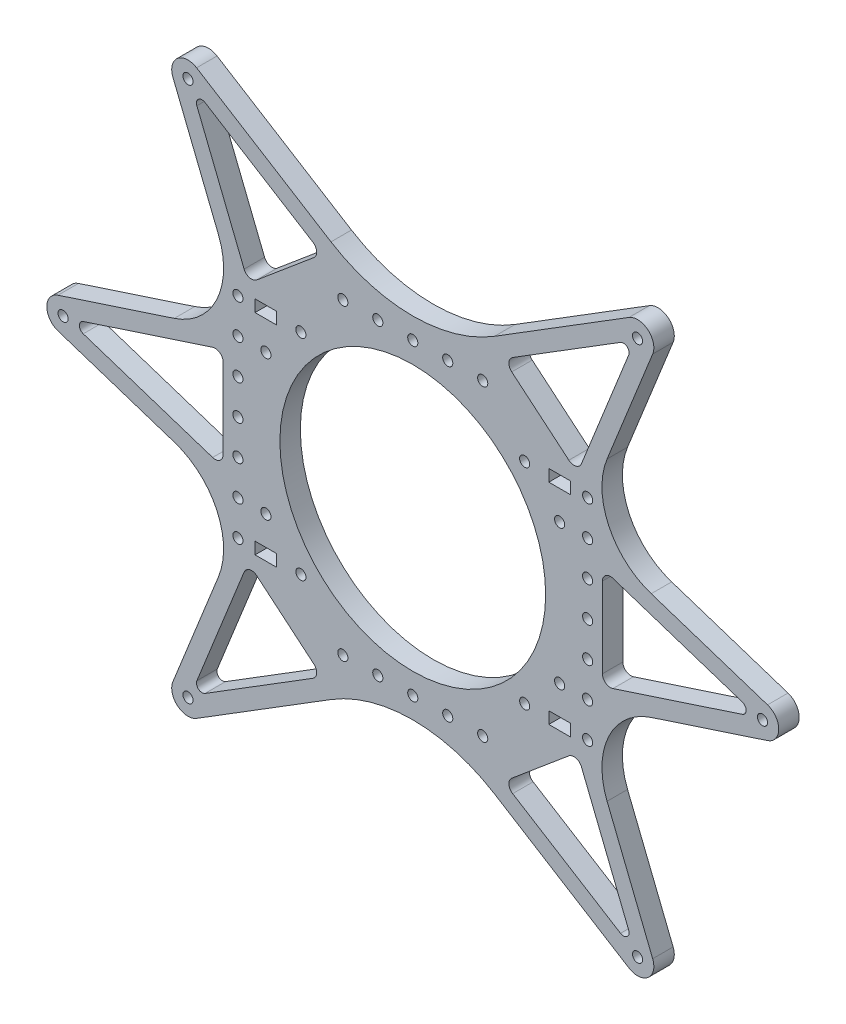
SolidWorks part; units mm, degrees
material "Acrylic (Medium-high impact)"
ref_plane "Front Plane" through (0, 0, 0) normal (0, 0, 1) x (1, 0, 0)
ref_plane "Top Plane" through (0, 0, 0) normal (0, 1, 0) x (1, 0, 0)
ref_plane "Right Plane" through (0, 0, 0) normal (1, 0, 0) x (0, 0, -1)
sketch "Sketch1" plane through (0, 0, 0) normal (0, 0, 1) x (1, 0, 0)
  line L0 (-447622.4345, 422.8828) -> (448935.6268, 422.8828) construction
  line L1 (587.9953, 497.7534) -> (601.0264, 465.2697)
  line L2 (698.5962, 452.8828) -> (698.5962, 392.8828) construction
  line L3 (653.3971, 419.0702) -> (-31485.9834, -37883.1519) construction
  line L4 (701.6962, 394.5828) -> (695.4962, 391.1828) construction
  line L5 (701.6962, 391.1828) -> (695.4962, 394.5828) construction
  line L6 (594.8522, 494.09) -> (608.3693, 460.3949)
  line L7 (594.7755, 503.4426) -> (633.2109, 479.5572)
  line L8 (597.1925, 496.0537) -> (628.0285, 476.8909)
  line L9 (594.8522, 494.09) -> (597.1925, 496.0537) construction
  line L10 (701.6962, 391.1828) -> (695.4962, 391.1828)
  line L11 (695.4962, 394.5828) -> (695.4962, 391.1828)
  line L12 (701.6962, 394.5828) -> (695.4962, 394.5828)
  line L13 (594.7755, 503.4426) -> (587.9953, 497.7534) construction
  line L14 (628.2915, 473.1954) -> (611.963, 459.4942)
  line L15 (608.3693, 460.3949) -> (628.0285, 476.8909) construction
  line L16 (701.6962, 394.5828) -> (701.6962, 391.1828)
  line L17 (-343.4038, 422.8828) -> (49656.5962, 422.8828) construction
  line L18 (648.8948, 432.061) -> (-31490.4849, 38734.2822) construction
  line L19 (-347.3366, 472.8828) -> (49652.6634, 472.8828) construction
  line L20 (-347.2527, 372.8828) -> (49652.7473, 372.8828) construction
  line L21 (562.3601, 421.3552) -> (599.3601, 409.2322)
  line L22 (602.3601, 434.3594) -> (602.3601, 411.4062)
  line L23 (555.1462, 427.3082) -> (555.1462, 418.4573) construction
  line L24 (562.3601, 424.4103) -> (599.3601, 436.5334)
  line L25 (599.3601, 409.2322) -> (599.3601, 436.5334) construction
  line L26 (555.1462, 427.3082) -> (588.4064, 438.2059)
  line L27 (562.3601, 421.3552) -> (562.3601, 424.4103) construction
  line L28 (555.1462, 418.4573) -> (588.4064, 407.5596)
  line L29 (594.8522, 351.6756) -> (608.3693, 385.3706)
  line L30 (594.7755, 342.3229) -> (633.2109, 366.2084)
  line L31 (611.963, 386.2714) -> (628.2915, 372.5702)
  line L32 (611.4962, 451.1828) -> (617.6962, 454.5828) construction
  line L33 (611.4962, 454.5828) -> (617.6962, 451.1828) construction
  line L34 (597.1925, 349.7118) -> (594.8522, 351.6756) construction
  line L35 (587.9953, 348.0122) -> (594.7755, 342.3229) construction
  line L36 (628.0285, 368.8746) -> (608.3693, 385.3706) construction
  line L37 (597.1925, 349.7118) -> (628.0285, 368.8746)
  line L38 (587.9953, 348.0122) -> (601.0264, 380.4959)
  line L39 (611.4962, 391.1828) -> (617.6962, 394.5828) construction
  line L40 (701.6962, 454.5828) -> (695.4962, 451.1828) construction
  line L41 (611.4962, 394.5828) -> (617.6962, 391.1828) construction
  line L42 (614.5962, 452.8828) -> (614.5962, 392.8828) construction
  line L43 (701.6962, 451.1828) -> (695.4962, 454.5828) construction
  line L44 (685.1639, 368.8746) -> (704.8231, 385.3706) construction
  line L45 (725.1971, 348.0122) -> (718.4169, 342.3229) construction
  line L46 (715.9998, 349.7118) -> (718.3402, 351.6756) construction
  line L47 (750.8323, 421.3552) -> (750.8323, 424.4103) construction
  line L48 (713.8323, 409.2322) -> (713.8323, 436.5334) construction
  line L49 (758.0462, 427.3082) -> (758.0462, 418.4573) construction
  line L50 (704.8231, 460.3949) -> (685.1639, 476.8909) construction
  line L51 (718.4169, 503.4426) -> (725.1971, 497.7534) construction
  line L52 (718.3402, 494.09) -> (715.9998, 496.0537) construction
  line L53 (611.4962, 454.5828) -> (617.6962, 454.5828)
  line L54 (617.6962, 451.1828) -> (617.6962, 454.5828)
  line L55 (611.4962, 451.1828) -> (617.6962, 451.1828)
  line L56 (701.6962, 451.1828) -> (701.6962, 454.5828)
  line L57 (701.6962, 451.1828) -> (695.4962, 451.1828)
  line L58 (695.4962, 451.1828) -> (695.4962, 454.5828)
  line L59 (701.6962, 454.5828) -> (695.4962, 454.5828)
  line L60 (725.1971, 348.0122) -> (712.166, 380.4959)
  line L61 (715.9998, 349.7118) -> (685.1639, 368.8746)
  line L62 (701.2294, 386.2714) -> (684.9009, 372.5702)
  line L63 (718.4169, 342.3229) -> (679.9814, 366.2084)
  line L64 (718.3402, 351.6756) -> (704.8231, 385.3706)
  line L65 (758.0462, 418.4573) -> (724.786, 407.5596)
  line L66 (758.0462, 427.3082) -> (724.786, 438.2059)
  line L67 (750.8323, 424.4103) -> (713.8323, 436.5334)
  line L68 (710.8323, 434.3594) -> (710.8323, 411.4062)
  line L69 (750.8323, 421.3552) -> (713.8323, 409.2322)
  line L70 (611.4962, 451.1828) -> (611.4962, 454.5828)
  line L71 (684.9009, 473.1954) -> (701.2294, 459.4942)
  line L72 (611.4962, 394.5828) -> (611.4962, 391.1828)
  line L73 (611.4962, 394.5828) -> (617.6962, 394.5828)
  line L74 (617.6962, 394.5828) -> (617.6962, 391.1828)
  line L75 (715.9998, 496.0537) -> (685.1639, 476.8909)
  line L76 (718.4169, 503.4426) -> (679.9814, 479.5572)
  line L77 (718.3402, 494.09) -> (704.8231, 460.3949)
  line L78 (725.1971, 497.7534) -> (712.166, 465.2697)
  line L79 (611.4962, 391.1828) -> (617.6962, 391.1828)
  line L80 (706.5962, 432.8828) -> (698.5962, 432.8828) construction
  line L81 (706.5962, 422.8828) -> (706.5962, 432.8828) construction
  line L82 (656.5962, 378.8828) -> (646.5962, 378.8828) construction
  line L83 (656.5962, 466.8828) -> (646.5962, 466.8828) construction
  line L111 (656.5962, -513.6368) -> (656.5962, 49486.3632) construction
  arc A0 (597.1925, 496.0537) -> (594.8522, 494.09) centre (596.3441, 494.6884) ccw
  arc A1 (587.9953, 497.7534) -> (594.7755, 503.4426) centre (592.3174, 499.4872) cw
  circle A2 centre (592.3174, 499.4872) radius 1.45
  arc A4 (608.3693, 460.3949) -> (611.963, 459.4942) centre (610.4925, 461.2467) ccw
  arc A5 (628.2915, 473.1954) -> (628.0285, 476.8909) centre (626.821, 474.9479) ccw
  circle A6 centre (592.3174, 499.4872) radius 4.6569 construction
  circle A7 centre (706.5962, 432.8828) radius 1.45
  circle A8 centre (706.5962, 442.8828) radius 1.45
  circle A9 centre (706.5962, 452.8828) radius 1.45
  circle A10 centre (706.5962, 392.8828) radius 1.45
  arc A11 (555.1462, 418.4573) -> (555.1462, 427.3082) centre (556.5962, 422.8828) cw
  circle A12 centre (556.5962, 422.8828) radius 1.45
  circle A13 centre (646.5962, 378.8828) radius 1.45
  circle A14 centre (556.5962, 422.8828) radius 4.6569 construction
  arc A15 (562.3601, 424.4103) -> (562.3601, 421.3552) centre (562.8606, 422.8828) ccw
  circle A16 centre (656.5962, 422.8828) radius 38
  circle A18 centre (636.5962, 378.8828) radius 1.45
  arc A19 (602.3601, 434.3594) -> (599.3601, 436.5334) centre (600.0724, 434.3594) ccw
  circle A20 centre (706.5962, 402.8828) radius 1.45
  arc A21 (599.3601, 409.2322) -> (602.3601, 411.4062) centre (600.0724, 411.4062) ccw
  circle A22 centre (656.5962, 466.8828) radius 1.45
  circle A24 centre (592.3174, 346.2783) radius 4.6569 construction
  arc A25 (628.0285, 368.8746) -> (628.2915, 372.5702) centre (626.821, 370.8177) ccw
  arc A27 (594.7755, 342.3229) -> (587.9953, 348.0122) centre (592.3174, 346.2783) cw
  arc A28 (594.8522, 351.6756) -> (597.1925, 349.7118) centre (596.3441, 351.0771) ccw
  arc A29 (611.963, 386.2714) -> (608.3693, 385.3706) centre (610.4925, 384.5189) ccw
  circle A31 centre (592.3174, 346.2783) radius 1.45
  circle A32 centre (706.5962, 412.8828) radius 1.45
  arc A33 (588.4064, 407.5596) -> (601.0264, 380.4959) centre (582.0351, 388.1144) cw
  circle A34 centre (656.5962, 378.8828) radius 1.45
  arc A35 (588.4064, 438.2059) -> (601.0264, 465.2697) centre (582.0351, 457.6512) ccw
  circle A37 centre (698.5962, 442.8828) radius 1.45
  circle A38 centre (698.5962, 402.8828) radius 1.45
  arc A39 (633.2109, 366.2084) -> (656.5962, 372.8828) centre (656.5962, 328.5778) cw
  arc A40 (633.2109, 479.5572) -> (656.5962, 472.8828) centre (656.5962, 517.1878) ccw
  circle A41 centre (720.8749, 346.2783) radius 4.6569 construction
  circle A42 centre (756.5962, 422.8828) radius 4.6569 construction
  circle A44 centre (646.5962, 466.8828) radius 1.45
  circle A45 centre (636.5962, 466.8828) radius 1.45
  circle A46 centre (720.8749, 499.4872) radius 4.6569 construction
  circle A48 centre (676.5962, 466.8828) radius 1.45
  circle A49 centre (666.5962, 466.8828) radius 1.45
  circle A50 centre (706.5962, 422.8828) radius 1.45
  arc A51 (679.9814, 479.5572) -> (656.5962, 472.8828) centre (656.5962, 517.1878) cw
  arc A52 (679.9814, 366.2084) -> (656.5962, 372.8828) centre (656.5962, 328.5778) ccw
  circle A53 centre (688.5962, 452.8828) radius 1.45
  circle A54 centre (688.5962, 392.8828) radius 1.45
  arc A55 (724.786, 438.2059) -> (712.166, 465.2697) centre (731.1572, 457.6512) cw
  arc A56 (724.786, 407.5596) -> (712.166, 380.4959) centre (731.1572, 388.1144) ccw
  circle A57 centre (624.5962, 392.8828) radius 1.45
  circle A58 centre (720.8749, 346.2783) radius 1.45
  arc A59 (701.2294, 386.2714) -> (704.8231, 385.3706) centre (702.6999, 384.5189) cw
  arc A60 (718.3402, 351.6756) -> (715.9998, 349.7118) centre (716.8483, 351.0771) cw
  arc A61 (718.4169, 342.3229) -> (725.1971, 348.0122) centre (720.8749, 346.2783) ccw
  arc A62 (685.1639, 368.8746) -> (684.9009, 372.5702) centre (686.3714, 370.8177) cw
  arc A63 (713.8323, 409.2322) -> (710.8323, 411.4062) centre (713.12, 411.4062) cw
  arc A64 (710.8323, 434.3594) -> (713.8323, 436.5334) centre (713.12, 434.3594) cw
  circle A65 centre (676.5962, 378.8828) radius 1.45
  arc A66 (750.8323, 424.4103) -> (750.8323, 421.3552) centre (750.3318, 422.8828) cw
  circle A67 centre (666.5962, 378.8828) radius 1.45
  circle A68 centre (756.5962, 422.8828) radius 1.45
  arc A69 (758.0462, 418.4573) -> (758.0462, 427.3082) centre (756.5962, 422.8828) ccw
  circle A70 centre (624.5962, 452.8828) radius 1.45
  circle A71 centre (606.5962, 422.8828) radius 1.45
  arc A74 (684.9009, 473.1954) -> (685.1639, 476.8909) centre (686.3714, 474.9479) cw
  arc A75 (704.8231, 460.3949) -> (701.2294, 459.4942) centre (702.6999, 461.2467) cw
  circle A76 centre (720.8749, 499.4872) radius 1.45
  arc A77 (725.1971, 497.7534) -> (718.4169, 503.4426) centre (720.8749, 499.4872) ccw
  arc A78 (715.9998, 496.0537) -> (718.3402, 494.09) centre (716.8483, 494.6884) cw
  circle A79 centre (614.5962, 402.8828) radius 1.45
  circle A80 centre (614.5962, 442.8828) radius 1.45
  circle A81 centre (606.5962, 412.8828) radius 1.45
  circle A83 centre (606.5962, 402.8828) radius 1.45
  circle A84 centre (606.5962, 392.8828) radius 1.45
  circle A85 centre (606.5962, 452.8828) radius 1.45
  circle A86 centre (606.5962, 442.8828) radius 1.45
  circle A87 centre (606.5962, 432.8828) radius 1.45
  circle A279 centre (626.5962, 466.8828) radius 1.45 [skipped]
  circle A282 centre (626.5962, 378.8828) radius 1.45 [skipped]
  circle A283 centre (698.5962, 422.8828) radius 1.45 [skipped]
  circle A284 centre (698.5962, 432.8828) radius 1.45 [skipped]
  circle A285 centre (698.5962, 412.8828) radius 1.45 [skipped]
  point P2 (620.1272, 466.3448)
  point P4 (604.6798, 472.924)
  point P5 (610.6788, 407.5004)
  point P6 (604.4937, 430.5743)
  point P7 (590.1096, 382.987)
  point P9 (656.5962, 422.8828)
  point P10 (592.2236, 451.9603)
  point P12 (560.2236, 451.9603)
  point P13 (615.5787, 412.0526)
  point P15 (596.4648, 452.5325)
  point P16 (593.7956, 519.1439)
  point P18 (562.0153, 451.7438)
  point P19 (589.324, 503.0546)
  point P21 (557.1601, 445.912)
  point P22 (691.7574, 496.0365)
  point P23 (586.2073, 519.1355)
  point P25 (698.5962, 452.8828)
  point P27 (593.4054, 384.161)
  point P31 (706.9167, 384.1702)
  point P32 (709.3005, 386.1481)
  point P33 (712.3266, 520.5499)
  point P34 (710.2125, 451.5766)
  point P37 (593.7956, 519.1439)
  point P38 (704.5328, 382.1922)
  point P40 (675.1867, 401.4708)
  point P41 (685.2778, 409.8289)
  point P43 (705.5495, 376.706)
  point P44 (637.2651, 404.097)
  point P46 (743.1543, 445.9191)
  point P47 (656.5962, 422.8828)
  point P48 (685.1467, 493.2598)
  point P49 (742.2125, 451.5766)
  point P53 (695.1768, 484.8286)
  point P55 (708.8884, 517.1528)
  point P56 (706.5155, 519.1439)
  point P57 (714.1038, 519.1355)
  point P64 (708.6406, 384.393)
  point P66 (665.171, 499.4399)
  point P67 (704.1427, 521.135)
  point P80 (602.3601, 422.8828)
  point P86 (499.5503, 435.3778)
  point P106 (620.1272, 379.4208)
  point P114 (563.3616, 328.8714)
  point P127 (698.5962, 422.8828)
  point P132 (656.5962, 460.8828)
  point P136 (656.5962, 465.4328)
  point P143 (704.687, 438.4721)
  point P145 (738.2906, 448.6533)
  point P146 (704.7346, 451.575)
  point P147 (738.2991, 451.7509)
  point P148 (738.3077, 454.8484)
  point P244 (749.8308, 328.8714)
  point P245 (693.0651, 379.4208)
  point P246 (710.8323, 422.8828)
  point P247 (698.5962, 422.8828)
  point P248 (723.8684, 503.0546)
  point P249 (693.0651, 466.3448)
  dimension "D2" = 2.9
  dimension "D3" = 6.2644
  dimension "D6" = 4
  dimension "D9" = 4
  dimension "D7" = 4
  dimension "D11" = 100
  dimension "D12" = 5
  dimension "D5" = 10
  dimension "D19" = 50
  dimension "D20" = 100
  dimension "D25" = 6.2644
  dimension "D13" = 3
  dimension "D15" = 37
  dimension "D18" = 42
  dimension "D23" = 10
  dimension "D28" = 10
  dimension "D39" = 3.4
  dimension "D37" = 2.9
  dimension "D38" = 76
  dimension "D40" = 4.55
  dimension "D8" = 50
  dimension "D10" = 30
  dimension "D14" = 50
  dimension "D16" = 37
  dimension "D17" = 2
  dimension "D21" = 44
  dimension "D22" = 35
  dimension "D24" = 5
  dimension "D26" = 3
  dimension "D27" = 8
  dimension "D29" = 5
  dimension "D30" = 6.2644
  dimension "D31" = 3
  dimension "D32" = 37
  dimension "D33" = 10
  dimension "D34" = 100
  dimension "D35" = 10
  dimension "D36" = 5
  dimension "D41" = 6.2
extrude "Boss-Extrude1" add sketch "Sketch1" along normal blind 5.85
